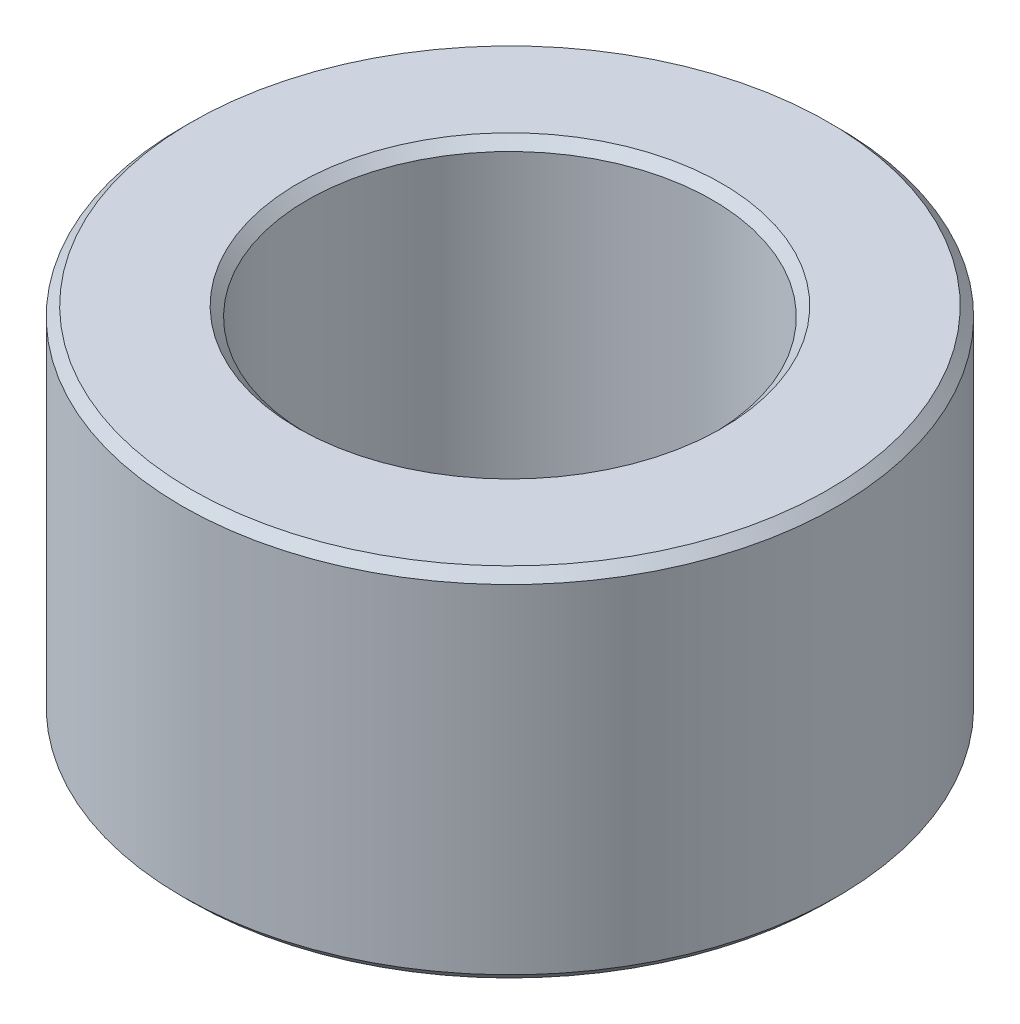
SolidWorks part; units mm, degrees
material "PVC Rigid"
ref_plane "Front Plane" through (0, 0, 0) normal (0, 0, 1) x (1, 0, 0)
ref_plane "Top Plane" through (0, 0, 0) normal (0, 1, 0) x (1, 0, 0)
ref_plane "Right Plane" through (0, 0, 0) normal (1, 0, 0) x (0, 0, -1)
sketch "Sketch2" plane through (0, 0, 0) normal (0, 1, 0) x (1, 0, 0)
  circle A0 centre (0, 0) radius 8.636
  dimension "D1" = 17.272
extrude "Extrude-Thin1" add sketch "Sketch2" along normal mid plane 9.4 thin thin type one direction reverse wall 3.302
chamfer "Chamfer1" distance 0.25 angle 45 4 edges at (5.334, -4.7, 0) (0, -4.7, 8.636) (5.334, 4.7, 0) (0, 4.7, 8.636)
